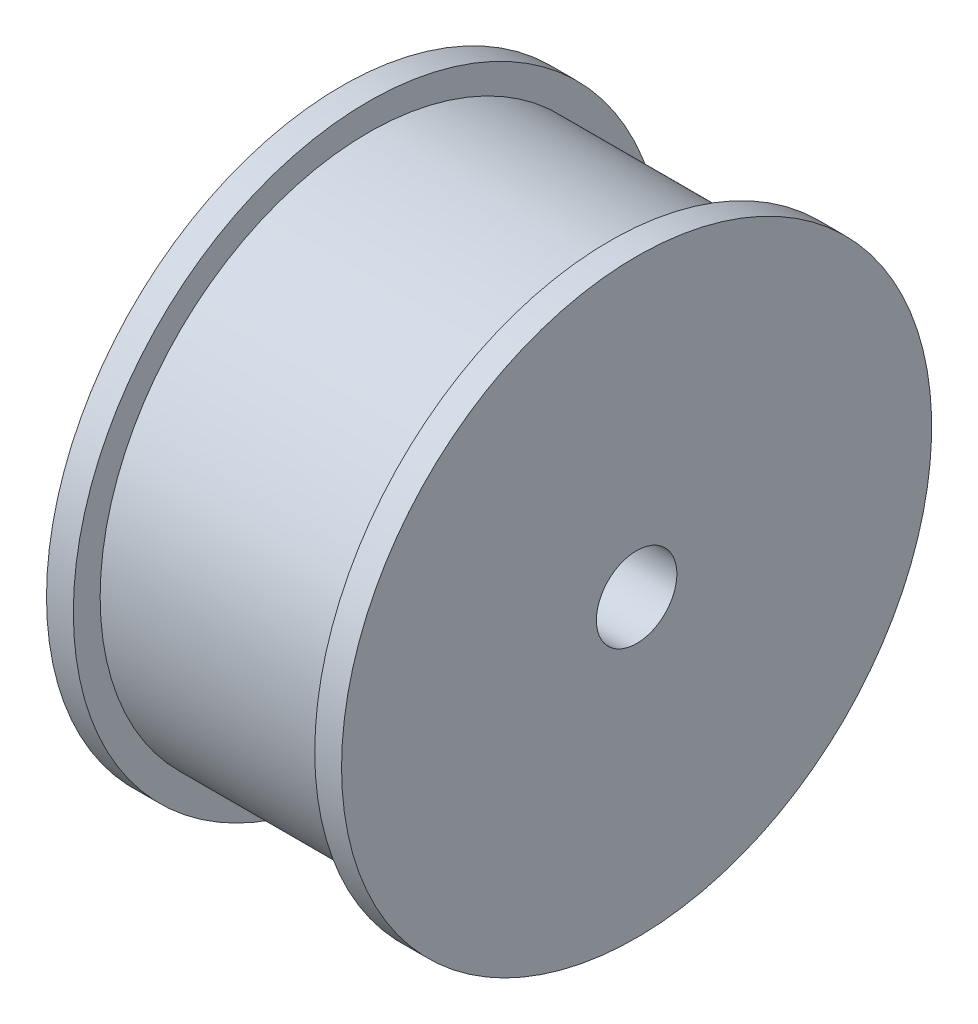
SolidWorks part; units mm, degrees
ref_plane "Front Plane" through (0, 0, 0) normal (0, 0, 1) x (1, 0, 0)
ref_plane "Top Plane" through (0, 0, 0) normal (0, 1, 0) x (1, 0, 0)
ref_plane "Right Plane" through (0, 0, 0) normal (1, 0, 0) x (0, 0, -1)
sketch "Sketch1" plane through (0, 0, 0) normal (0, 1, 0) x (1, 0, 0)
  line L2 (0, 1.5) -> (0, 11)
  line L3 (0, 11) -> (1, 11)
  line L4 (11, 11) -> (11, 1.5)
  line L5 (11, 1.5) -> (0, 1.5)
  line L6 (1, 11) -> (1, 10)
  line L7 (1, 10) -> (10, 10)
  line L8 (10, 10) -> (10, 11)
  line L9 (10, 11) -> (11, 11)
  line L10 (5.5, 17.4029) -> (5.5, 10.4549) construction
  line L11 (0, 0) -> (18, 0) construction
  dimension "D1" = 1.5
  dimension "D4" = 11
  dimension "D5" = 1
  dimension "D6" = 1
  dimension "D7" = 11
revolve "Revolve1" add sketch "Sketch1" angle 360 about L11
